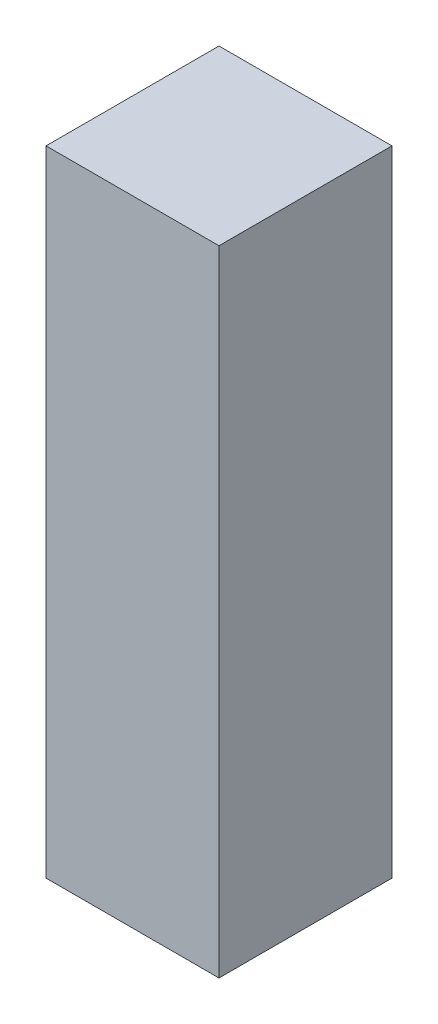
SolidWorks part; units mm, degrees
ref_plane "Front Plane" through (0, 0, 0) normal (0, 0, 1) x (1, 0, 0)
ref_plane "Top Plane" through (0, 0, 0) normal (0, 1, 0) x (1, 0, 0)
ref_plane "Right Plane" through (0, 0, 0) normal (1, 0, 0) x (0, 0, -1)
other "Configuration Table"
sketch "Sketch1" plane through (0, 0, 0) normal (0, 0, 1) x (1, 0, 0)
  line L1 (320, 560) -> (380, 560)
  line L2 (320, 560) -> (320, 780)
  line L3 (320, 780) -> (380, 780)
  line L4 (380, 560) -> (380, 780)
extrude "OVEN_kesme_aktuator_24V_1500N_1" add sketch "Sketch1" against normal blind 60 from offset 270 separate body
